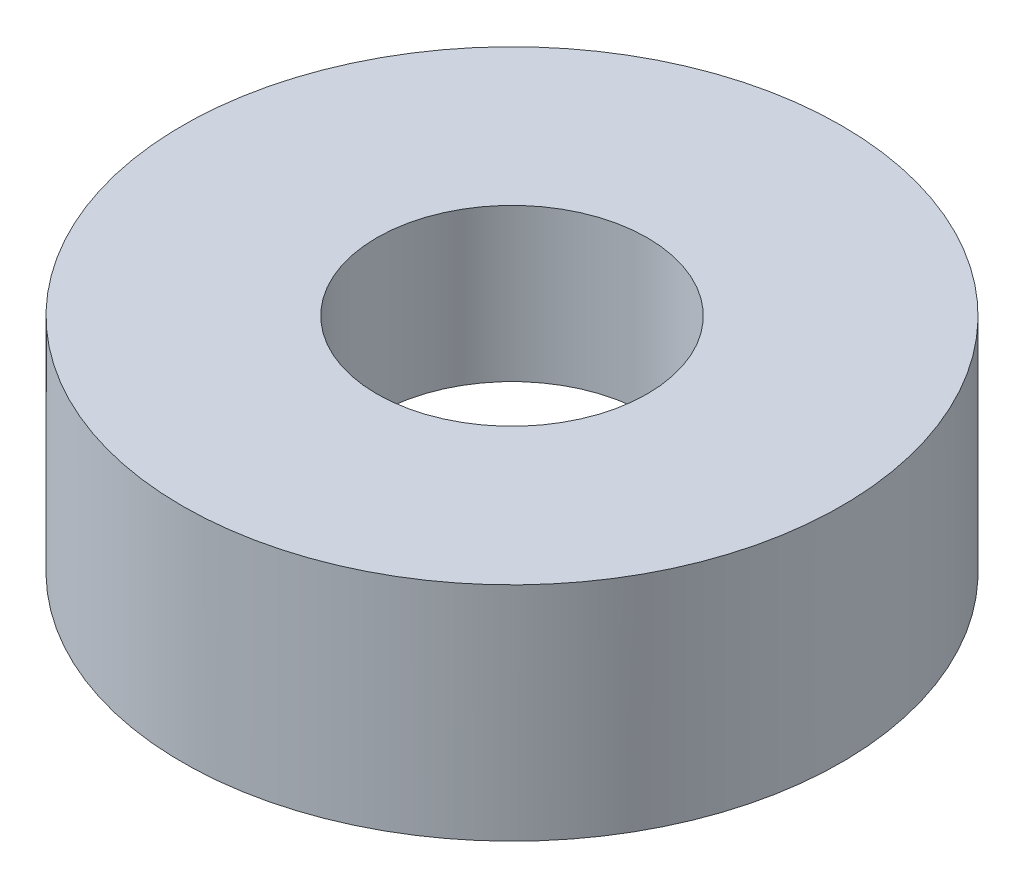
SolidWorks part; units mm, degrees
ref_plane "Ebene vorne" through (0, 0, 0) normal (0, 0, 1) x (1, 0, 0)
ref_plane "Ebene oben" through (0, 0, 0) normal (0, 1, 0) x (1, 0, 0)
ref_plane "Ebene rechts" through (0, 0, 0) normal (1, 0, 0) x (0, 0, -1)
sketch "Skizze1" plane through (0, 0, 0) normal (0, 1, 0) x (1, 0, 0)
  circle A0 centre (0, 0) radius 4.75
  circle A1 centre (0, 0) radius 1.95
  dimension "D1" = 9.5
  dimension "D2" = 3.9
extrude "Aufsatz-Linear austragen1" add sketch "Skizze1" along normal blind 2.2
sketch "Skizze2" plane through (0, 0, 0) normal (0, -1, 0) x (1, 0, 0)
  circle A0 centre (0, 0) radius 4.75
  circle A1 centre (0, 0) radius 4.25
  circle A2 centre (0, 0) radius 4.75 construction
  dimension "D1" = 8.5
extrude "Aufsatz-Linear austragen2" add sketch "Skizze2" along normal blind 1
